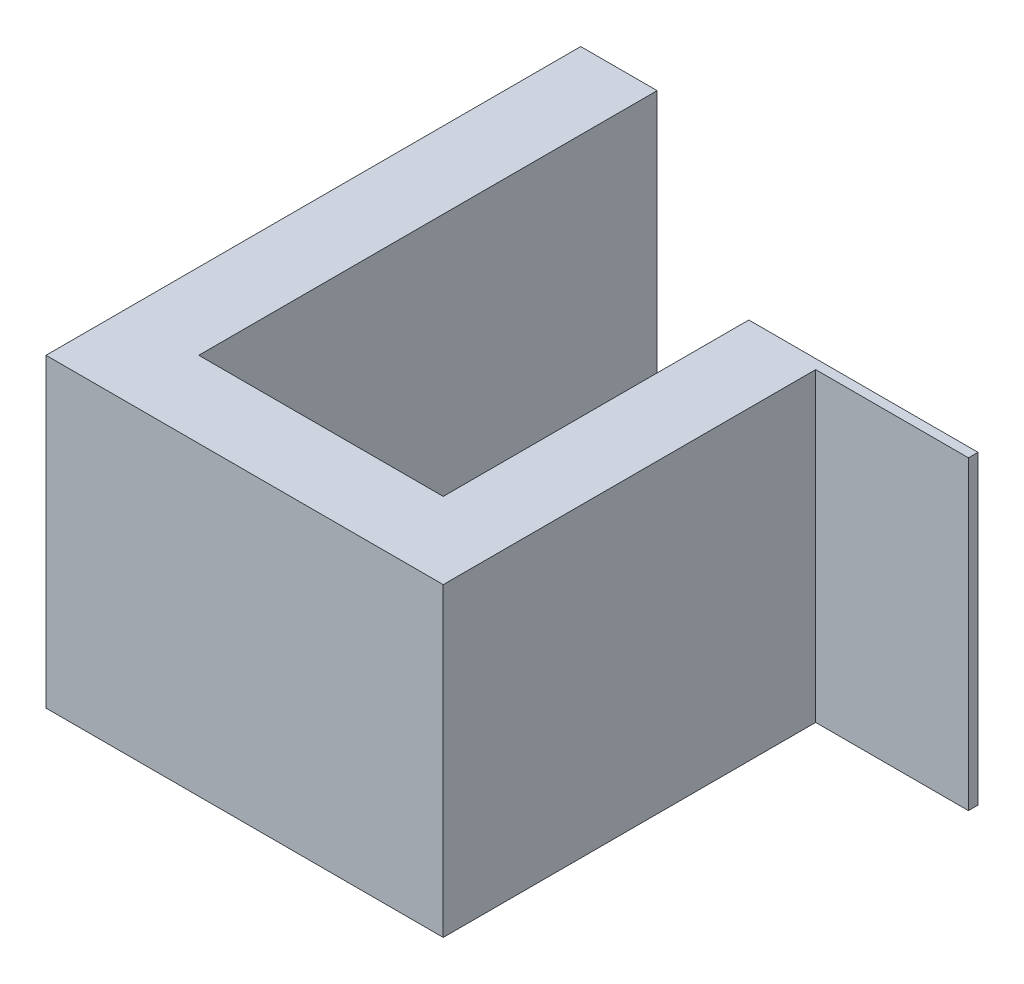
SolidWorks part; units mm, degrees
material "1060 Alloy"
ref_plane "Front Plane" through (0, 0, 0) normal (0, 0, 1) x (1, 0, 0)
ref_plane "Top Plane" through (0, 0, 0) normal (0, 1, 0) x (1, 0, 0)
ref_plane "Right Plane" through (0, 0, 0) normal (1, 0, 0) x (0, 0, -1)
sketch "Sketch1" plane through (0, 0, 0) normal (0, 1, 0) x (1, 0, 0)
  line L0 (-13.335, -15.875) -> (3.175, -15.875)
  line L1 (0, 0) -> (3.175, 0)
  line L2 (0, 0) -> (0, -12.7)
  line L4 (3.175, 0) -> (3.175, -15.875)
  line L7 (0, -12.7) -> (-10.16, -12.7)
  line L10 (-10.16, -12.7) -> (-10.16, 6.35)
  line L11 (-10.16, 6.35) -> (-13.335, 6.35)
  line L12 (-13.335, -15.875) -> (-13.335, 6.35)
  line L13 (0, -12.7) -> (0, -15.875) construction
  line L15 (3.175, 0) -> (9.525, 0)
  line L16 (3.175, 0) -> (3.175, -0.3969)
  line L17 (3.175, -0.3969) -> (9.525, -0.3969)
  line L18 (9.525, 0) -> (9.525, -0.3969)
  dimension "D1" = 12.7
  dimension "D2" = 10.16
  dimension "D3" = 19.05
  dimension "D4" = 3.175
  dimension "D5" = 6.35
  dimension "D6" = 0.3969
extrude "Boss-Extrude1" add sketch "Sketch1" along normal blind 12.7 contours L13 L7 L10 L11 L12 L0 | L2 L13 L0 L4 L1 | L15 L18 L17 L16
